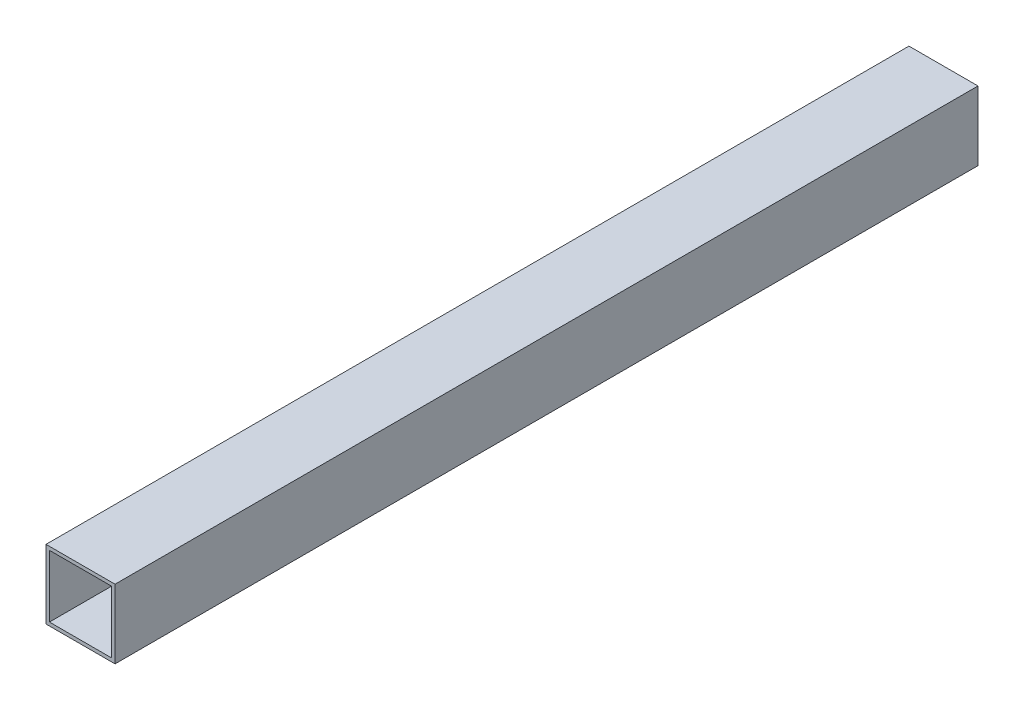
SolidWorks part; units mm, degrees
material "1060-H18 Barra (SS)"
ref_plane "Alzado" through (0, 0, 0) normal (0, 0, 1) x (1, 0, 0)
ref_plane "Planta" through (0, 0, 0) normal (0, 1, 0) x (1, 0, 0)
ref_plane "Vista lateral" through (0, 0, 0) normal (1, 0, 0) x (0, 0, -1)
sketch "Croquis1" plane through (0, 0, 0) normal (0, 0, 1) x (1, 0, 0)
  line L1 (20, -20) -> (-20, -20)
  line L2 (20, -20) -> (20, 20)
  line L3 (20, 20) -> (-20, 20)
  line L4 (-20, -20) -> (-20, 20)
  line L5 (20, -20) -> (-20, 20) construction
  line L6 (20, 20) -> (-20, -20) construction
  point P0 (0, 0)
  dimension "D1" = 40
  dimension "D2" = 40
extrude "Extruir-Lámina1" add sketch "Croquis1" along normal blind 500 thin
